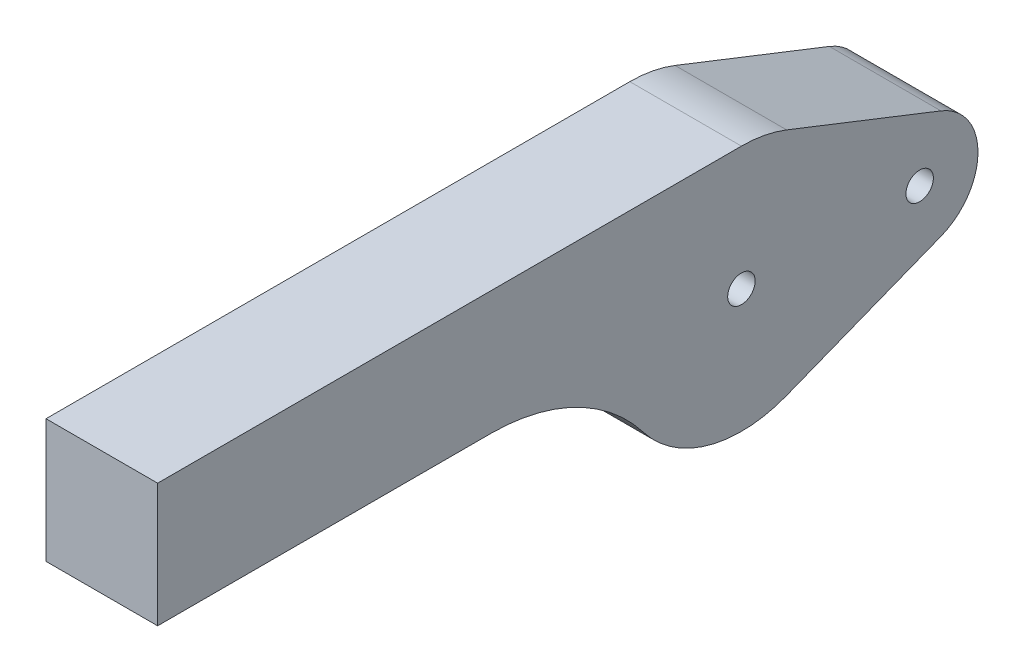
SolidWorks part; units mm, degrees
ref_plane "前视基准面" through (0, 0, 0) normal (0, 0, 1) x (1, 0, 0)
ref_plane "上视基准面" through (0, 0, 0) normal (0, 1, 0) x (1, 0, 0)
ref_plane "右视基准面" through (0, 0, 0) normal (1, 0, 0) x (0, 0, -1)
other "Configuration Table"
sketch "草图1" plane through (0, 0, 0) normal (1, 0, 0) x (0, 0, -1)
  line L0 (-30, 0) -> (30, 0)
  line L1 (-30, -4.725) -> (30, -4.725)
  line L2 (-30, -4.725) -> (-30, 4.725)
  line L3 (-30, 4.725) -> (30, 4.725)
  line L4 (30, -4.725) -> (30, 4.725)
  line L5 (-30, -4.725) -> (30, 4.725) construction
  line L6 (-30, 4.725) -> (30, -4.725) construction
  line L7 (26.5, 0) -> (30, 0)
  line L8 (12.52, 0) -> (30, 0)
  line L9 (27.0553, -3.9552) -> (15.8135, -8.3757)
  line L10 (-30, 4.725) -> (30, 4.725)
  line L11 (-30, 4.725) -> (-30, 9.45)
  line L12 (-30, 9.45) -> (30, 9.45)
  line L13 (30, 4.725) -> (30, 9.45)
  line L14 (27.0553, 3.9552) -> (15.8135, 8.3757)
  line L15 (12.52, 9) -> (-30, 9)
  circle A0 centre (25.5, 0) radius 1
  circle A1 centre (12.52, 0) radius 1
  circle A2 centre (12.52, 0) radius 9
  circle A3 centre (25.5, 0) radius 4.25
  point P0 (0, 0)
  dimension "D3" = 2
  dimension "D5" = 2
  dimension "D7" = 18
  dimension "D8" = 8.5
  dimension "D1" = 9.45
  dimension "D2" = 60
  dimension "D4" = 3.5
  dimension "D6" = 17.48
  dimension "D9" = 9.45
extrude "凸台-拉伸1" add sketch "草图1" along normal blind 8.13 contours A2 L15 L11 L3 | L10 A2 | A3 A2 L10 L0 A1 L8 | L0 A3 A2 A0 | A3 L14 L3 A2 | A2 L3 L14 | A2 L3 L2 L0 | A2 A3 L0 A0 | A3 L8 A1 L0 A2 L1 | L1 A2 | A3 A2 L1 L9 | L0 A3 A2 | A2 A3 L0 | A2 L9 L1
fillet "圆角1" radius 14 1 edges at (4.065, 0, -3.52)
